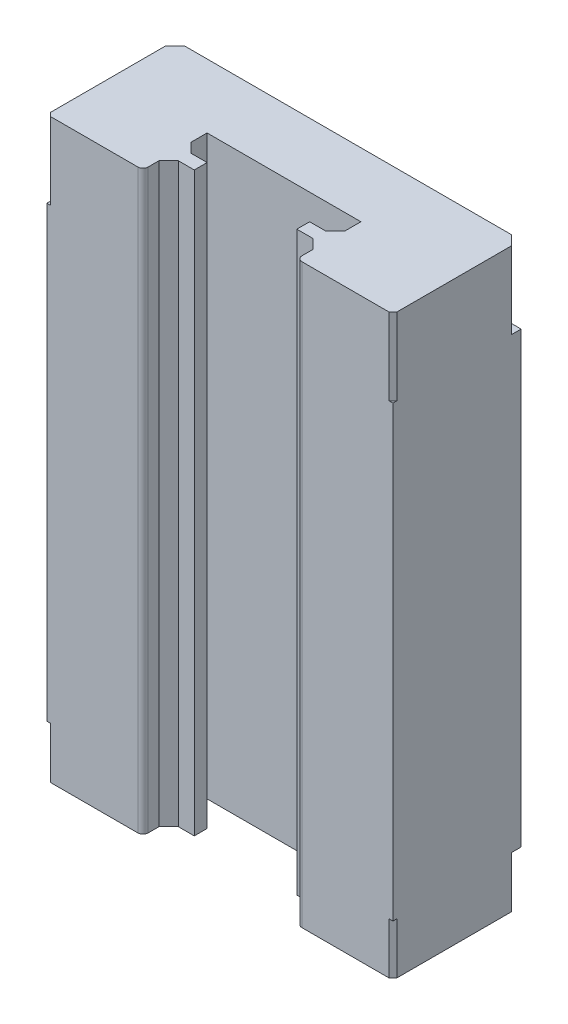
SolidWorks part; units mm, degrees
ref_plane "Front Plane" through (0, 0, 0) normal (0, 0, 1) x (1, 0, 0)
ref_plane "Top Plane" through (0, 0, 0) normal (0, 1, 0) x (1, 0, 0)
ref_plane "Right Plane" through (0, 0, 0) normal (1, 0, 0) x (0, 0, -1)
sketch "Sketch2" plane through (0, 0, 0) normal (0, 1, 0) x (1, 0, 0)
  line L0 (0, 0) -> (0, -16.1976) construction
  line L1 (-13.5, 5) -> (13.5, 5)
  line L2 (-13.5, 5) -> (-13.5, -5)
  line L3 (-13.5, -5) -> (-6, -5)
  line L4 (13.5, 5) -> (13.5, -5)
  line L5 (-13.5, 5) -> (13.5, -5) construction
  line L6 (-13.5, -5) -> (13.5, 5) construction
  line L8 (-6, -5) -> (-6, -3.75)
  line L9 (-6, 0) -> (6, 0)
  line L10 (-6, -5) -> (-6, -3)
  line L11 (-5.25, -2) -> (-4, -2)
  line L12 (-4, -2) -> (-4, -3)
  line L13 (-4, -3) -> (-5.25, -3)
  line L14 (-6, -1.25) -> (-6, 0)
  line L15 (-5.25, -2) -> (-6, -1.25)
  line L16 (-5.25, -3) -> (-6, -3.75)
  line L17 (6, -5) -> (6, -3.75)
  line L18 (5.25, -3) -> (6, -3.75)
  line L19 (4, -3) -> (5.25, -3)
  line L20 (4, -2) -> (4, -3)
  line L21 (5.25, -2) -> (4, -2)
  line L22 (5.25, -2) -> (6, -1.25)
  line L23 (6, -1.25) -> (6, 0)
  line L25 (6, -5) -> (13.5, -5)
  point P0 (0, 0)
  point P13 (-6, -2)
  point P28 (0, 0)
  dimension "D1" = 10
  dimension "D2" = 27
  dimension "D4" = 5
  dimension "D5" = 3
  dimension "D6" = 1
  dimension "D7" = 2
extrude "Boss-Extrude1" add sketch "Sketch2" along normal blind 45 contours L8 L16 L13 L12 L11 L15 L14 L9 L23 L22 L21 L20 L19 L18 L17 L25 L4 L1 L2 L3
fillet "Fillet1" radius 0.4 2 edges at (6, 22.5, 5) (-6, 22.5, 5)
sketch "Sketch3" plane through (0, 0, -5) normal (0, 0, -1) x (-1, 0, 0)
  line L0 (0, 0) -> (0, 23.5) construction
  line L6 (-10, 33.5) -> (10, 13.5) construction
  line L7 (-10, 13.5) -> (10, 33.5) construction
  circle A0 centre (10, 33.5) radius 1.5
  circle A1 centre (-10, 33.5) radius 1.5
  circle A2 centre (-10, 13.5) radius 1.5
  circle A3 centre (10, 13.5) radius 1.5
  dimension "D1" = 23.5
  dimension "D2" = 20
  dimension "D3" = 20
extrude "Cut-Extrude3" cut sketch "Sketch3" against normal blind 5
sketch "Sketch4" plane through (0, 45, 0) normal (0, 1, 0) x (1, 0, 0)
  line L0 (-13.5, 5) -> (-13.5, 4.25)
  line L1 (-13.5, 5) -> (-13.5, -5) construction
  line L2 (-13.5, 4.25) -> (-12.75, 5)
  line L3 (-13.5, 5) -> (13.5, 5) construction
  line L4 (-12.75, 5) -> (-13.5, 5)
  line L5 (0, 0) -> (0, -9.7064) construction
  line L6 (13.5, 4.25) -> (12.75, 5)
  line L7 (13.5, 5) -> (13.5, 4.25)
  line L8 (12.75, 5) -> (13.5, 5)
  line L9 (-13.5, -5) -> (-13.2, -5)
  line L10 (-13.5, -5) -> (-6.4, -5) construction
  line L11 (-13.2, -5) -> (-13.5, -4.7)
  line L12 (-13.5, -4.7) -> (-13.5, -5)
  line L13 (13.2, -5) -> (13.5, -4.7)
  line L14 (13.5, -5) -> (13.2, -5)
  line L15 (13.5, -4.7) -> (13.5, -5)
  dimension "D1" = 0.75
  dimension "D2" = 0.75
  dimension "D3" = 0.3
  dimension "D4" = 0.3
extrude "Cut-Extrude5" cut sketch "Sketch4" against normal blind 6
ref_plane "Plane2" through (0, 21.5, 0) normal (0, 1, 0) x (1, 0, 0)
mirror "Mirror1" about plane through (0, 21.5, 0) normal (0, 1, 0) of "Cut-Extrude5"
